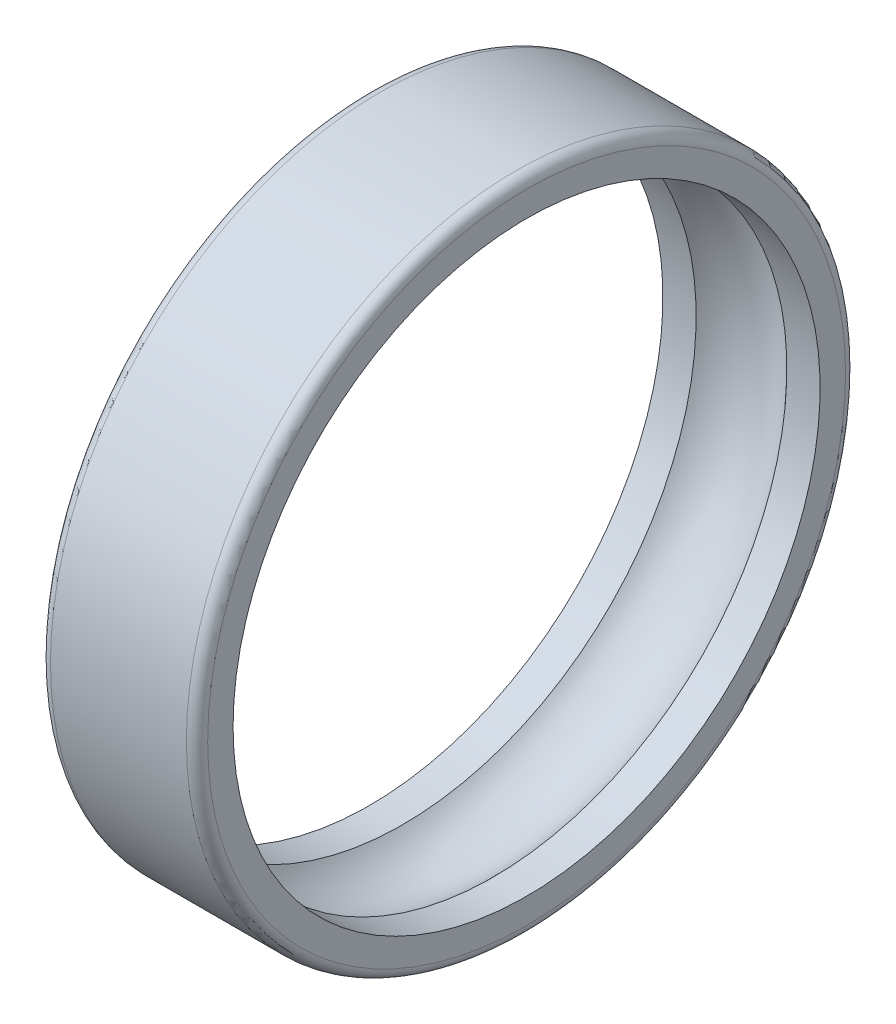
SolidWorks part; units mm, degrees
ref_plane "Front Plane" through (0, 0, 0) normal (0, 0, 1) x (1, 0, 0)
ref_plane "Top Plane" through (0, 0, 0) normal (0, 1, 0) x (1, 0, 0)
ref_plane "Right Plane" through (0, 0, 0) normal (1, 0, 0) x (0, 0, -1)
sketch "Sketch1" plane through (0, 0, 0) normal (0, 0, 1) x (1, 0, 0)
  line L0 (-92.3957, 0) -> (172.8877, 0) construction
  line L1 (0, 0) -> (0, 57.89) construction
  line L2 (-15.5, 57.89) -> (-8.9443, 57.89)
  line L3 (-15.5, 57.89) -> (-15.5, 65)
  line L4 (-15.5, 65) -> (15.5, 65)
  line L5 (15.5, 57.89) -> (15.5, 65)
  line L6 (8.9443, 57.89) -> (15.5, 57.89)
  arc A1 (-8.9443, 57.89) -> (8.9443, 57.89) centre (0, 49.89) cw
  dimension "D5" = 12
  dimension "D1" = 65
  dimension "D2" = 57.89
  dimension "D3" = 31
  dimension "D4" = 8
revolve "Revolve1" add sketch "Sketch1" angle 360 about L0
fillet "Fillet1" radius 2.1 2 edges at (15.5, 0, 65) (-15.5, 0, 65)
scale "Scale1" scale about centroid uniform scaling yes scale factor 0.22
scale "Scale2" scale about centroid uniform scaling yes scale factor 0.2
scale "Scale3" scale about centroid uniform scaling yes scale factor 3.84
